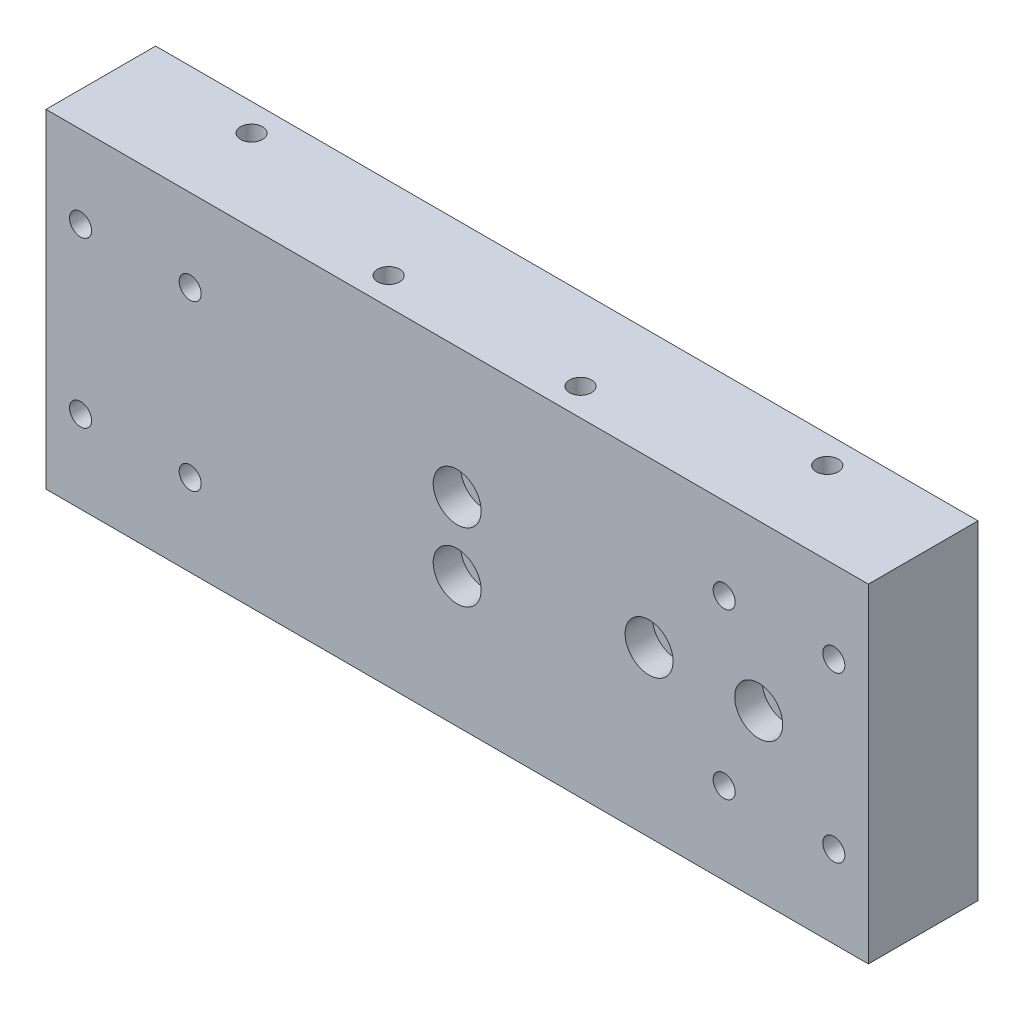
SolidWorks part; units mm, degrees
ref_plane "Front Plane" through (0, 0, 0) normal (0, 0, 1) x (1, 0, 0)
ref_plane "Top Plane" through (0, 0, 0) normal (0, 1, 0) x (1, 0, 0)
ref_plane "Right Plane" through (0, 0, 0) normal (1, 0, 0) x (0, 0, -1)
sketch "Sketch1" plane through (0, 0, 0) normal (0, 0, 1) x (1, 0, 0)
  line L0 (95.25, -38.1) -> (-95.25, 38.1) construction
  line L1 (-95.25, -38.1) -> (95.25, -38.1)
  line L2 (-95.25, -38.1) -> (-95.25, 38.1)
  line L3 (-95.25, 38.1) -> (95.25, 38.1)
  line L4 (95.25, -38.1) -> (95.25, 38.1)
  dimension "D1" = 190.5
  dimension "D2" = 76.2
extrude "Extrude1" add sketch "Sketch1" along normal mid plane 25.4
hole_wizard "Side-1/4-20 tapped hole master" positions "Sketch11" profile "Sketch10" tap size "1/4-20" standard "Ansi Inch"
sketch "Sketch11" plane through (0, -38.1, 0) normal (0, -1, 0) x (1, 0, 0)
  point P0 (22.225, 6.35)
  point P1 (66.675, -6.35)
  dimension "D1" = 22.225
  dimension "D2" = 66.675
  dimension "D3" = 6.35
  dimension "D4" = 6.35
sketch "Sketch10" plane through (22.225, -38.1, 6.35) normal (1, 0, 0) x (0, 0, -1)
  line L0 (0, 0) -> (0, 20.5838)
  line L1 (0, 20.5838) -> (2.5527, 19.05)
  line L2 (2.5527, 19.05) -> (2.5527, 0)
  line L5 (2.5527, 0) -> (0, 0)
  line L10 (0, 20.5838) -> (-2.5527, 19.05) construction
  line L11 (0, -6.35) -> (0, 107.95) construction
  dimension "Tap Drill Dia." = 5.1054
  dimension "Tap Drill Depth" = 19.05
  dimension "Drill Angle" = 118
cosmetic thread "Hole Thread1" parameters "D1"=12.7, "D2"=6.35
cosmetic thread "Hole Thread2" parameters "D1"=12.7, "D2"=6.35
mirror "Side-1/4-20 tapped hole mirror I" about plane through (0, 0, 0) normal (1, 0, 0) of "Side-1/4-20 tapped hole master"
mirror "Side-1/4-20 tapped hole mirror II" about plane through (0, 0, 0) normal (0, 1, 0) of "Side-1/4-20 tapped hole mirror I", "Side-1/4-20 tapped hole master"
hole_wizard "Top-1/4-20 tapped hoes" positions "Sketch15" profile "Sketch14" tap size "1/4-20" standard "Ansi Inch" end condition through all
sketch "Sketch15" plane through (0, 0, 12.7) normal (0, 0, 1) x (1, 0, 0)
  line L4 (-87.249, 19.05) -> (-61.849, 19.05) construction
  line L5 (-61.849, 19.05) -> (-61.849, -19.05) construction
  line L6 (87.249, 19.05) -> (61.849, 19.05) construction
  line L7 (61.849, 19.05) -> (61.849, -19.05) construction
  line L8 (0, 0) -> (61.849, 0) construction
  line L9 (0, 0) -> (-61.849, 0) construction
  line L10 (74.549, 19.05) -> (74.549, 62.1361) construction
  point P0 (-61.849, 19.05)
  point P1 (-61.849, -19.05)
  point P3 (-87.249, 19.05)
  point P5 (-87.249, -19.05)
  point P7 (87.249, 19.05)
  point P9 (87.249, -19.05)
  point P11 (61.849, 19.05)
  point P13 (61.849, -19.05)
  dimension "D1" = 25.4
  dimension "D2" = 74.549
  dimension "D3" = 19.05
  dimension "D4" = 19.05
sketch "Sketch14" plane through (-61.849, 19.05, 12.7) normal (1, 0, 0) x (0, -1, 0)
  line L0 (0, 0) -> (0, 25.4)
  line L1 (0, 25.4) -> (2.5527, 25.4)
  line L2 (2.5527, 25.4) -> (2.5527, 0)
  line L5 (2.5527, 0) -> (0, 0)
  line L11 (0, -6.35) -> (0, 107.95) construction
  dimension "Thru Tap Drill Dia." = 5.1054
  dimension "Thru Tap Drill Depth" = 25.4
cosmetic thread "Hole Thread3" parameters "D2"=6.35
cosmetic thread "Hole Thread4" parameters "D2"=6.35
cosmetic thread "Hole Thread5" parameters "D2"=6.35
cosmetic thread "Hole Thread6" parameters "D2"=6.35
cosmetic thread "Hole Thread7" parameters "D2"=6.35
cosmetic thread "Hole Thread8" parameters "D2"=6.35
cosmetic thread "Hole Thread9" parameters "D2"=6.35
cosmetic thread "Hole Thread10" parameters "D2"=6.35
hole_wizard "Busihing flexure coupling 1/4-20 bolt holes" positions "Sketch17" profile "Sketch16" counterbore size "1/4" standard "Ansi Inch" end condition through all
sketch "Sketch17" plane through (-12.1558, -9.3593, 12.7) normal (0, 0, -1) x (-1, 0, 0)
  line L0 (-82.0058, 9.3593) -> (-56.6058, 9.3593) construction
  line L1 (-69.3058, 22.0593) -> (-69.3058, 9.3593) construction
  line L2 (-69.3058, 9.3593) -> (-69.3058, -3.3407) construction
  circle A0 centre (-69.3058, 9.3593) radius 12.7 construction
  point P0 (-56.6058, 9.3593)
  point P1 (-82.0058, 9.3593)
  dimension "D1" = 57.15
  dimension "D2" = 25.4
sketch "Sketch16" plane through (44.45, 0, 12.7) normal (1, 0, 0) x (0, -1, 0)
  line L0 (0, 0) -> (0, 25.4)
  line L1 (0, 25.4) -> (3.3782, 25.4)
  line L3 (3.3782, 25.4) -> (3.3782, 6.35)
  line L4 (3.3782, 6.35) -> (5.5562, 6.35)
  line L5 (5.5562, 6.35) -> (5.5562, 0)
  line L7 (5.5562, 0) -> (0, 0)
  line L11 (0, -6.35) -> (0, 107.95) construction
  dimension "Thru Hole Dia." = 6.7564
  dimension "Thru Hole Depth" = 25.4
  dimension "C'Bore Dia." = 11.1125
  dimension "C'Bore Depth" = 6.35
hole_wizard "Lead screw 1/4 cap screw mounts" positions "Sketch19" profile "Sketch18" counterbore size "1/4" standard "Ansi Inch" end condition through all
sketch "Sketch19" plane through (36.4807, 13.8528, 12.7) normal (0, 0, -1) x (-1, 0, 0)
  line L4 (36.4807, -5.9153) -> (36.4807, -21.7903) construction
  point P1 (36.4807, -5.9153)
  point P3 (36.4807, -21.7903)
  dimension "D2" = 15.875
sketch "Sketch18" plane through (0, 7.9375, 12.7) normal (1, 0, 0) x (0, -1, 0)
  line L0 (0, 0) -> (0, 25.4)
  line L1 (0, 25.4) -> (3.3782, 25.4)
  line L3 (3.3782, 25.4) -> (3.3782, 6.35)
  line L4 (3.3782, 6.35) -> (5.5562, 6.35)
  line L5 (5.5562, 6.35) -> (5.5562, 0)
  line L7 (5.5562, 0) -> (0, 0)
  line L11 (0, -6.35) -> (0, 107.95) construction
  dimension "Thru Hole Dia." = 6.7564
  dimension "Thru Hole Depth" = 25.4
  dimension "C'Bore Dia." = 11.1125
  dimension "C'Bore Depth" = 6.35
